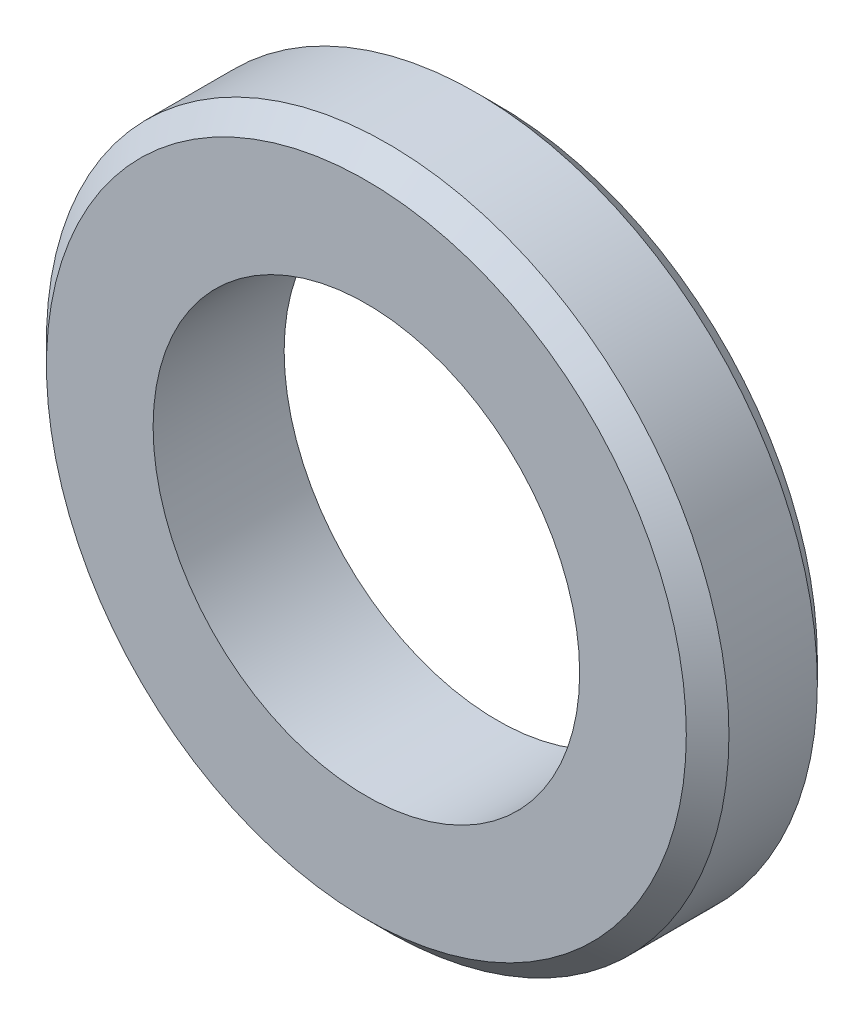
SolidWorks part; units mm, degrees
ref_plane "Front Plane" through (0, 0, 0) normal (0, 0, 1) x (1, 0, 0)
ref_plane "Top Plane" through (0, 0, 0) normal (0, 1, 0) x (1, 0, 0)
ref_plane "Right Plane" through (0, 0, 0) normal (1, 0, 0) x (0, 0, -1)
sketch "Sketch1" plane through (0, 0, 0) normal (0, 0, 1) x (1, 0, 0)
  circle A0 centre (0, 0) radius 12.7
  circle A1 centre (0, 0) radius 7.9375
  dimension "D1" = 25.4
  dimension "D2" = 15.875
extrude "Boss-Extrude1" add sketch "Sketch1" along normal blind 4.8768
chamfer "Chamfer1" distance 0.7937 angle 45 2 edges at (12.7, 0, 4.8768) (12.7, 0, 0)
ref_plane "Plane1" through (0, 0, 2.4384) normal (0, 0, -1) x (-1, 0, 0)
